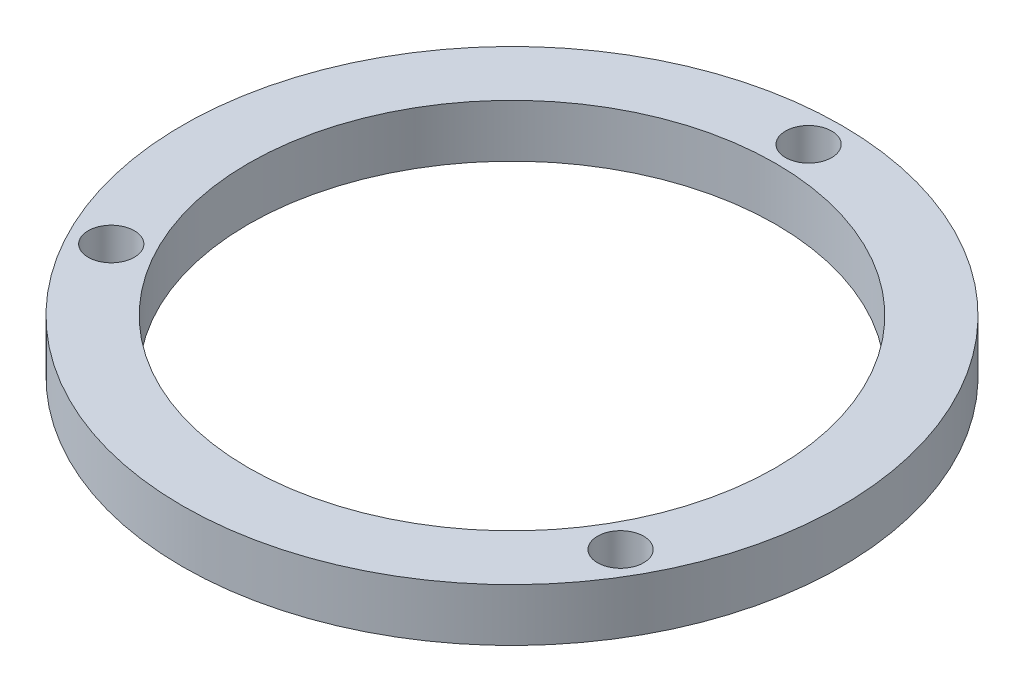
SolidWorks part; units mm, degrees
ref_plane "Ebene vorne" through (0, 0, 0) normal (0, 0, 1) x (1, 0, 0)
ref_plane "Ebene oben" through (0, 0, 0) normal (0, 1, 0) x (1, 0, 0)
ref_plane "Ebene rechts" through (0, 0, 0) normal (1, 0, 0) x (0, 0, -1)
sketch "Skizze2" plane through (0, 0, 0) normal (0, 1, 0) x (1, 0, 0)
  line L0 (0, 0) -> (43.3013, -25) construction
  line L1 (0, 0) -> (-44.2239, -23.3291) construction
  line L2 (0, 45) -> (0, -45) construction
  circle A0 centre (0, 0) radius 50
  circle A1 centre (0, 0) radius 45
  circle A2 centre (38.9711, -22.5) radius 2
  circle A3 centre (-39.8015, -20.9962) radius 2
  circle A4 centre (0, 45) radius 2
  circle A5 centre (0, -35) radius 2
  circle A6 centre (0, -27.5) radius 2
  dimension "D1" = 100
  dimension "D2" = 90
extrude "Aufsatz-Linear austragen1" add sketch "Skizze2" along normal blind 8 contours A4 A1 A3 A2 A6 A5 | A0 A4 A1 A2 A3
sketch "Skizze9" plane through (0, 8, 0) normal (0, 1, 0) x (1, 0, 0)
  line L2 (-6, -39.5312) -> (-6, -22.5312)
  line L3 (-6, -22.5312) -> (6, -22.5312)
  line L4 (6, -39.5312) -> (6, -22.5312)
  arc A0 (-6, -39.5312) -> (6, -39.5312) centre (0, 0) cw
  point P4 (0, -27.5)
extrude "Schnitt-Linear austragen2" cut sketch "Skizze9" against normal blind 3
sketch "Skizze10" plane through (0, 0, 0) normal (0, -1, 0) x (1, 0, 0)
  circle A2 centre (38.9711, 22.5) radius 3.5
  circle A3 centre (-39.8015, 20.9962) radius 3.5
  circle A4 centre (0, -45) radius 3.5
sketch "Skizze39" plane through (0, 0, 0) normal (0, -1, 0) x (-1, 0, 0)
  circle A0 centre (0, 0) radius 40
extrude "Schnitt-Linear austragen3" cut sketch "Skizze39" against normal blind 10
extrude "Schnitt-Linear austragen4" cut sketch "Skizze10" against normal blind 10
